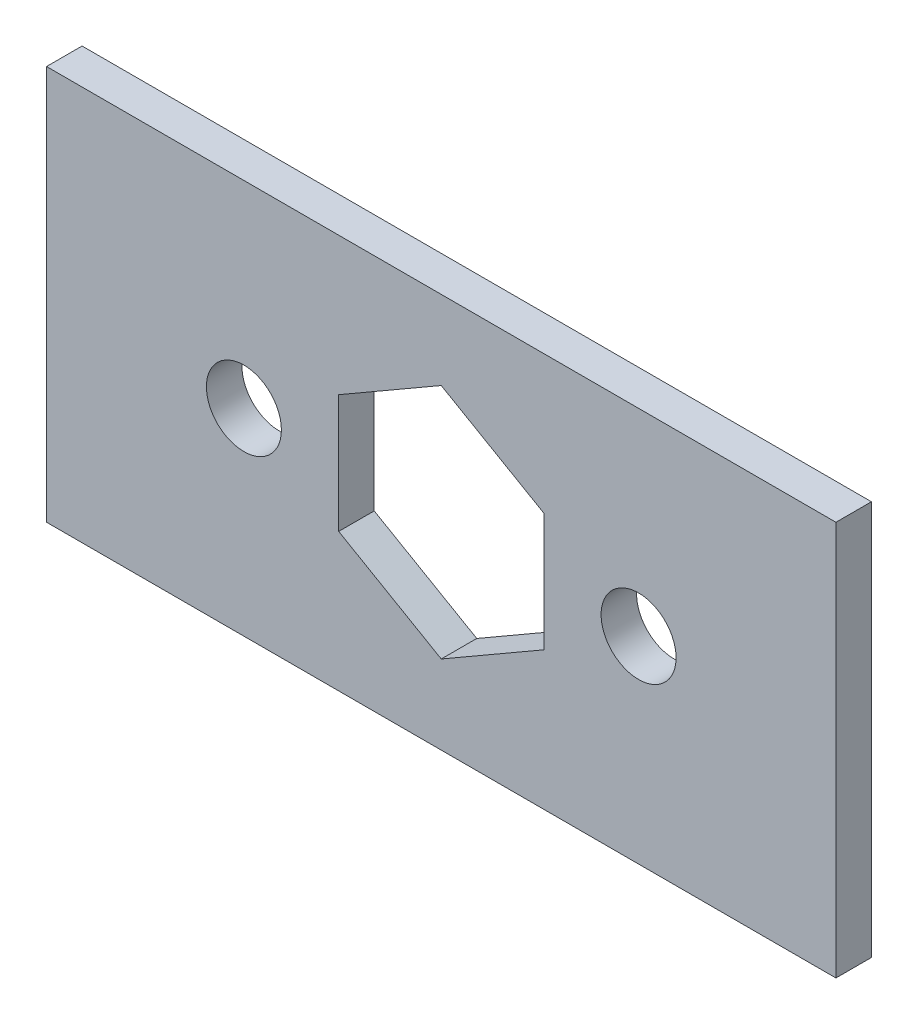
SolidWorks part; units mm, degrees
ref_plane "Front Plane" through (0, 0, 0) normal (0, 0, 1) x (1, 0, 0)
ref_plane "Top Plane" through (0, 0, 0) normal (0, 1, 0) x (1, 0, 0)
ref_plane "Right Plane" through (0, 0, 0) normal (1, 0, 0) x (0, 0, -1)
sketch "Sketch1" plane through (0, 0, 0) normal (0, 0, 1) x (1, 0, 0)
  line L1 (6.35, 3.6662) -> (0, 7.3323) construction
  line L2 (0, 7.3323) -> (-6.35, 3.6662) construction
  line L3 (-6.35, 3.6662) -> (-6.35, -3.6662) construction
  line L4 (-6.35, -3.6662) -> (0, -7.3323) construction
  line L5 (0, -7.3323) -> (6.35, -3.6662) construction
  line L6 (6.35, -3.6662) -> (6.35, 3.6662) construction
  line L7 (25.4, 12.7) -> (-25.4, 12.7)
  line L8 (25.4, 12.7) -> (25.4, -12.7)
  line L9 (25.4, -12.7) -> (-25.4, -12.7)
  line L10 (-25.4, 12.7) -> (-25.4, -12.7)
  line L11 (0, 7.62) -> (-6.5991, 3.81)
  line L12 (-6.5991, 3.81) -> (-6.5991, -3.81)
  line L13 (-6.5991, -3.81) -> (0, -7.62)
  line L14 (0, -7.62) -> (6.5991, -3.81)
  line L15 (6.5991, -3.81) -> (6.5991, 3.81)
  line L16 (6.5991, 3.81) -> (0, 7.62)
  circle A0 centre (0, 0) radius 6.35 construction
  circle A1 centre (-12.7, 0) radius 2.413
  circle A2 centre (12.7, 0) radius 2.413
  circle A3 centre (0, 0) radius 7.1438 construction
  circle A4 centre (0, 0) radius 6.5991 construction
  dimension "D9" = 4.826
  dimension "D10" = 4.826
  dimension "D11" = 14.2875
  dimension "D1" = 12.7
  dimension "D2" = 25.4
  dimension "D3" = 50.8
  dimension "D4" = 25.4
  dimension "D5" = 12.7
  dimension "D6" = 12.7
  dimension "D7" = 12.7
  dimension "D8" = 25.4
  dimension "D12" = 14.6647
  dimension "D13" = 15.24
extrude "Boss-Extrude1" add sketch "Sketch1" along normal mid plane 2.286
